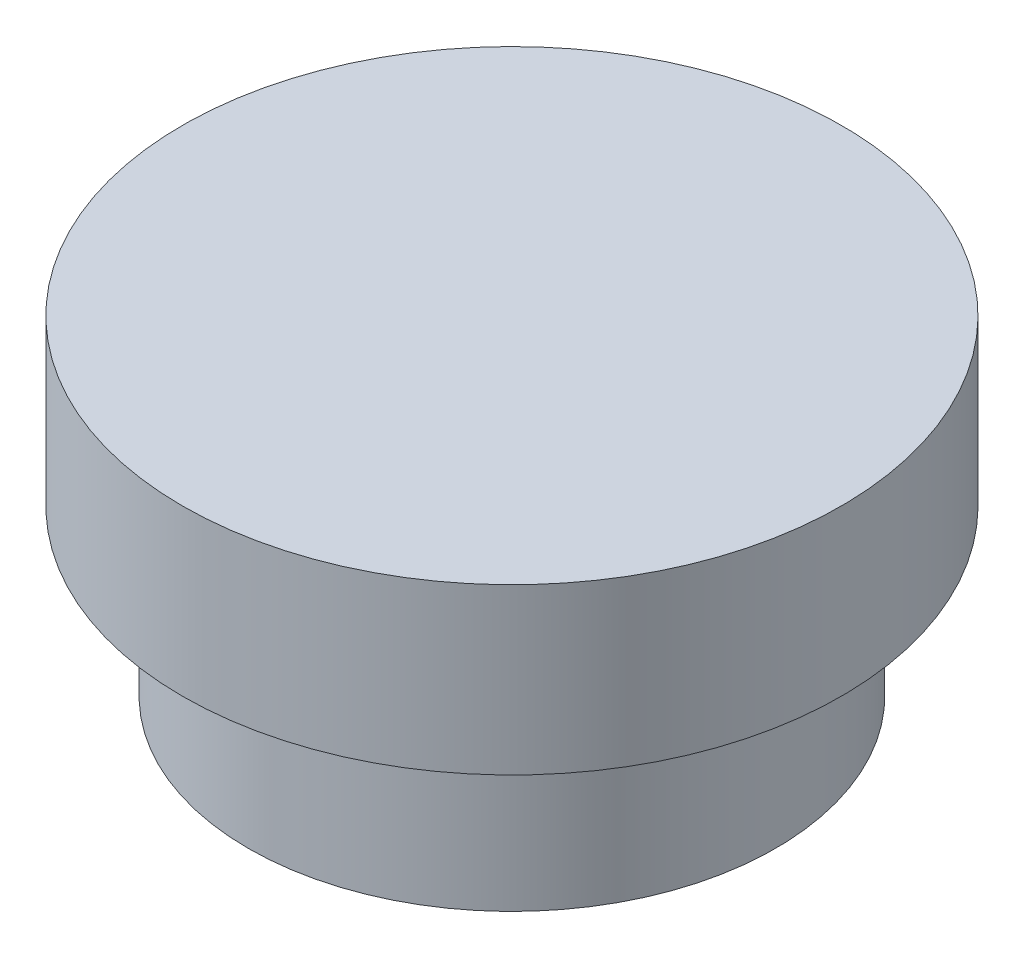
SolidWorks part; units mm, degrees
ref_plane "Front Plane" through (0, 0, 0) normal (0, 0, 1) x (1, 0, 0)
ref_plane "Top Plane" through (0, 0, 0) normal (0, 1, 0) x (1, 0, 0)
ref_plane "Right Plane" through (0, 0, 0) normal (1, 0, 0) x (0, 0, -1)
sketch "Sketch1" plane through (0, 0, 0) normal (0, 0, 1) x (1, 0, 0)
  line L0 (0, 16.3754) -> (0, -21.3177) construction
  line L1 (0, 0) -> (-10, 0)
  line L2 (-10, 0) -> (-10, -5)
  line L3 (-10, -5) -> (-8, -5)
  line L4 (-8, -5) -> (-8, -10)
  line L5 (-8, -10) -> (0, -10)
  line L6 (0, 0) -> (0, -10)
  dimension "D1" = 8
  dimension "D2" = 5
  dimension "D3" = 10
  dimension "D4" = 5
revolve "Revolve1" add sketch "Sketch1" angle 360 about L0
sketch "Sketch2" plane through (0, -10, 0) normal (0, -1, 0) x (1, 0, 0)
  line L0 (0, -10.8035) -> (0, 11.0541) construction
  line L1 (-16.5958, 0) -> (16.1917, 0) construction
